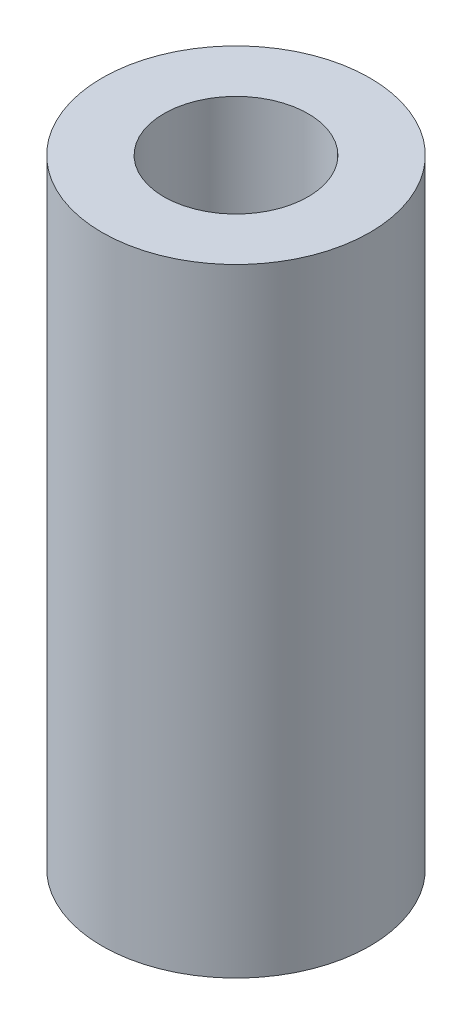
SolidWorks part; units mm, degrees
ref_plane "Front Plane" through (0, 0, 0) normal (0, 0, 1) x (1, 0, 0)
ref_plane "Top Plane" through (0, 0, 0) normal (0, 1, 0) x (1, 0, 0)
ref_plane "Right Plane" through (0, 0, 0) normal (1, 0, 0) x (0, 0, -1)
sketch "Sketch1" plane through (0, 0, 0) normal (0, 1, 0) x (1, 0, 0)
  circle A0 centre (0, 0) radius 1.75
  circle A1 centre (0, 0) radius 3.25
  dimension "D1" = 3.5
  dimension "D2" = 1.5
extrude "Boss-Extrude1" add sketch "Sketch1" along normal blind 15
